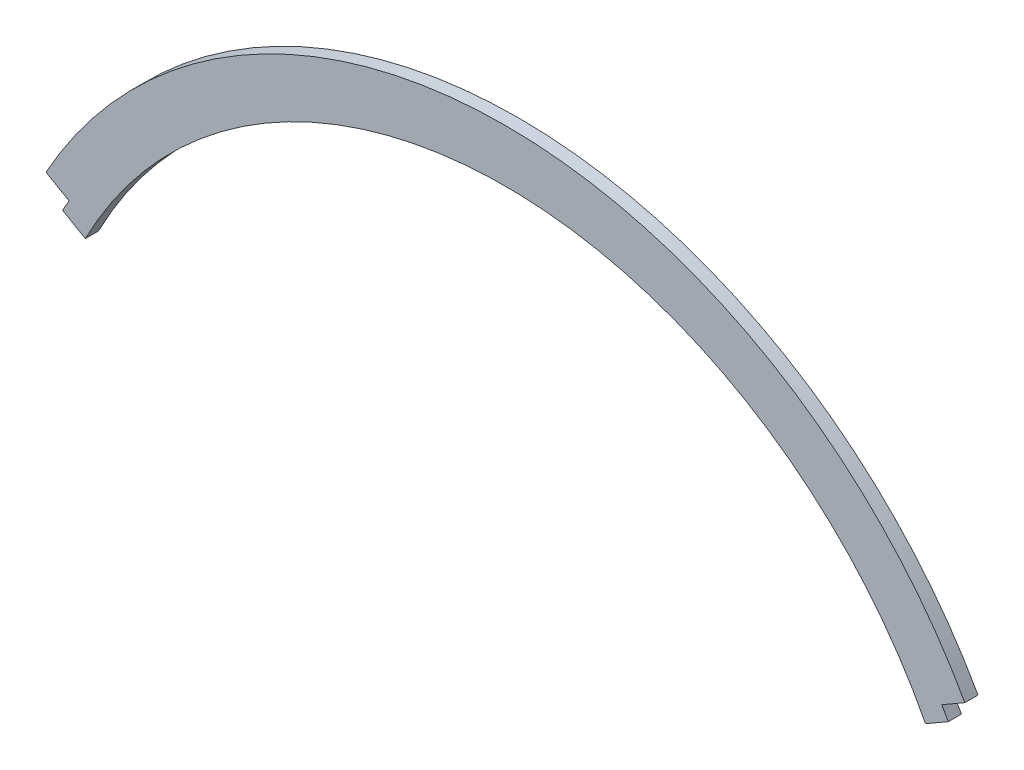
SolidWorks part; units mm, degrees
material "Balsa"
ref_plane "Front Plane" through (0, 0, 0) normal (0, 0, 1) x (1, 0, 0)
ref_plane "Top Plane" through (0, 0, 0) normal (0, 1, 0) x (1, 0, 0)
ref_plane "Right Plane" through (0, 0, 0) normal (1, 0, 0) x (0, 0, -1)
sketch "Sketch1" plane through (0, 0, 0) normal (0, 0, 1) x (1, 0, 0)
  line L0 (101.4846, 0) -> (0, -58.5922) construction
  line L1 (0, -58.5922) -> (-101.4846, 0) construction
  line L4 (-101.4846, 0) -> (-112.4934, 6.3559)
  line L5 (0, -58.5922) -> (0, 87.3988) construction
  line L6 (101.4846, 0) -> (112.4934, 6.3559)
  arc A0 (101.4846, 0) -> (-101.4846, 0) centre (0, -52.5867) ccw
  arc A3 (112.4934, 6.3559) -> (-112.4934, 6.3559) centre (0, -52.5867) ccw
  arc A4 (112.7607, 5.843) -> (-112.7607, 5.843) centre (0, -52.5867) ccw construction
  dimension "D2" = 114.3
  dimension "D3" = 202.9692
  dimension "D1" = 120
  dimension "D5" = 12.7
extrude "Boss-Extrude1" add sketch "Sketch1" along normal blind 3.175
sketch "Sketch2" plane through (0, 0, 3.175) normal (0, 0, 1) x (1, 0, 0)
  line L0 (112.4934, 6.3559) -> (106.989, 3.178)
  line L1 (101.4846, 0) -> (112.4934, 6.3559) construction
  line L2 (106.989, 3.178) -> (105.4015, 5.9276)
  line L3 (105.4015, 5.9276) -> (110.9842, 9.1507)
  line L4 (0, 0) -> (0, 21.5849) construction
  arc A0 (112.4934, 6.3559) -> (-112.4934, 6.3559) centre (0, -52.5867) ccw construction
  arc A1 (112.4934, 6.3559) -> (110.9842, 9.1507) centre (0, -52.5867) ccw
  dimension "D1" = 3.175
extrude "Cut-Extrude1" cut sketch "Sketch2" against normal through all both and the other way through all
mirror "Mirror1" about plane through (0, 0, 0) normal (1, 0, 0) of "Cut-Extrude1"
